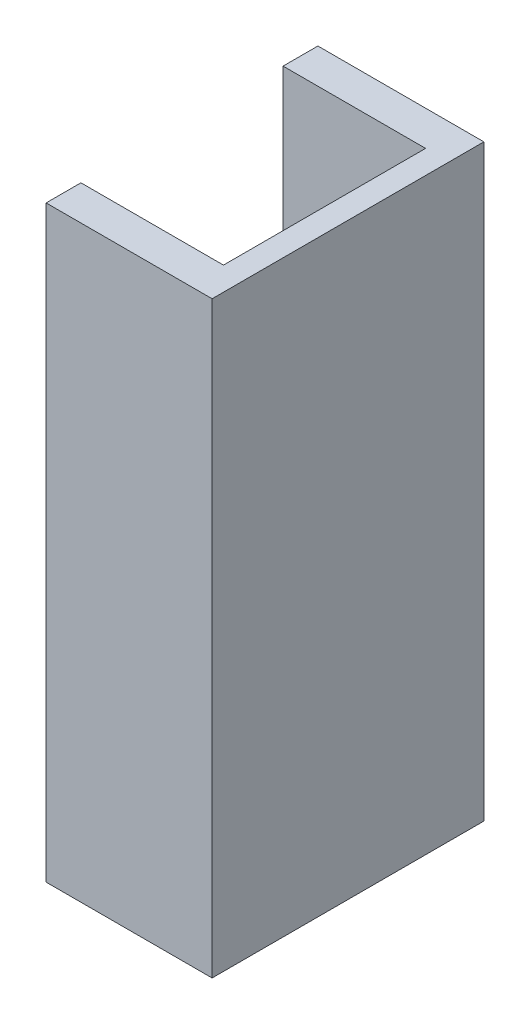
SolidWorks part; units mm, degrees
material "1060 Alloy"
ref_plane "Front Plane" through (0, 0, 0) normal (0, 0, 1) x (1, 0, 0)
ref_plane "Top Plane" through (0, 0, 0) normal (0, 1, 0) x (1, 0, 0)
ref_plane "Right Plane" through (0, 0, 0) normal (1, 0, 0) x (0, 0, -1)
sketch "Sketch1" plane through (0, 0, 0) normal (0, 1, 0) x (1, 0, 0)
  line L0 (-7.75, 25.41) -> (-7.75, 18.9)
  line L1 (-18.9, -18.9) -> (-17.3231, -18.9) construction
  line L2 (-18.9, -18.9) -> (-18.9, 18.9) construction
  line L3 (-7.75, 18.9) -> (18.9, 18.9)
  line L4 (18.9, -18.9) -> (18.9, 18.9)
  line L5 (-18.9, -18.9) -> (18.9, 18.9) construction
  line L6 (-18.9, 18.9) -> (18.9, -18.9) construction
  line L7 (-7.75, -25.41) -> (23.29, -25.41)
  line L8 (-23.29, -25.41) -> (-23.29, 25.41) construction
  line L9 (-7.75, 25.41) -> (23.29, 25.41)
  line L10 (23.29, -25.41) -> (23.29, 25.41)
  line L11 (-23.29, -25.41) -> (23.29, 25.41) construction
  line L12 (-23.29, 25.41) -> (23.29, -25.41) construction
  line L13 (-23.29, -25.41) -> (-7.75, -25.41) construction
  line L14 (-17.3231, -18.9) -> (-7.75, -18.9) construction
  line L15 (-7.75, -18.9) -> (18.9, -18.9)
  line L16 (-18.9, 18.9) -> (-17.3231, 18.9) construction
  line L17 (-17.3231, 18.9) -> (-7.75, 18.9) construction
  line L18 (-23.29, 25.41) -> (-7.75, 25.41) construction
  line L19 (-7.75, 7.75) -> (-7.75, -7.75) construction
  line L20 (-7.75, -7.75) -> (-7.75, -8.4555) construction
  line L21 (-7.75, -8.4555) -> (-7.75, -18.9) construction
  line L22 (-7.75, -18.9) -> (-7.75, -25.41)
  line L23 (-7.75, 8.4555) -> (-7.75, 7.75) construction
  line L24 (-7.75, 18.9) -> (-7.75, 8.4555) construction
  point P0 (0, 0)
  point P6 (0, 0)
  dimension "D1" = 37.8
  dimension "D4" = 37.8
  dimension "D2" = 7.75
  dimension "D3" = 50.82
  dimension "D5" = 4.39
extrude "Boss-Extrude1" add sketch "Sketch1" against normal blind 110 contours L9 L10 L7 L8
equation "\"D4@Sketch1\"=\"D1@Sketch1\""
